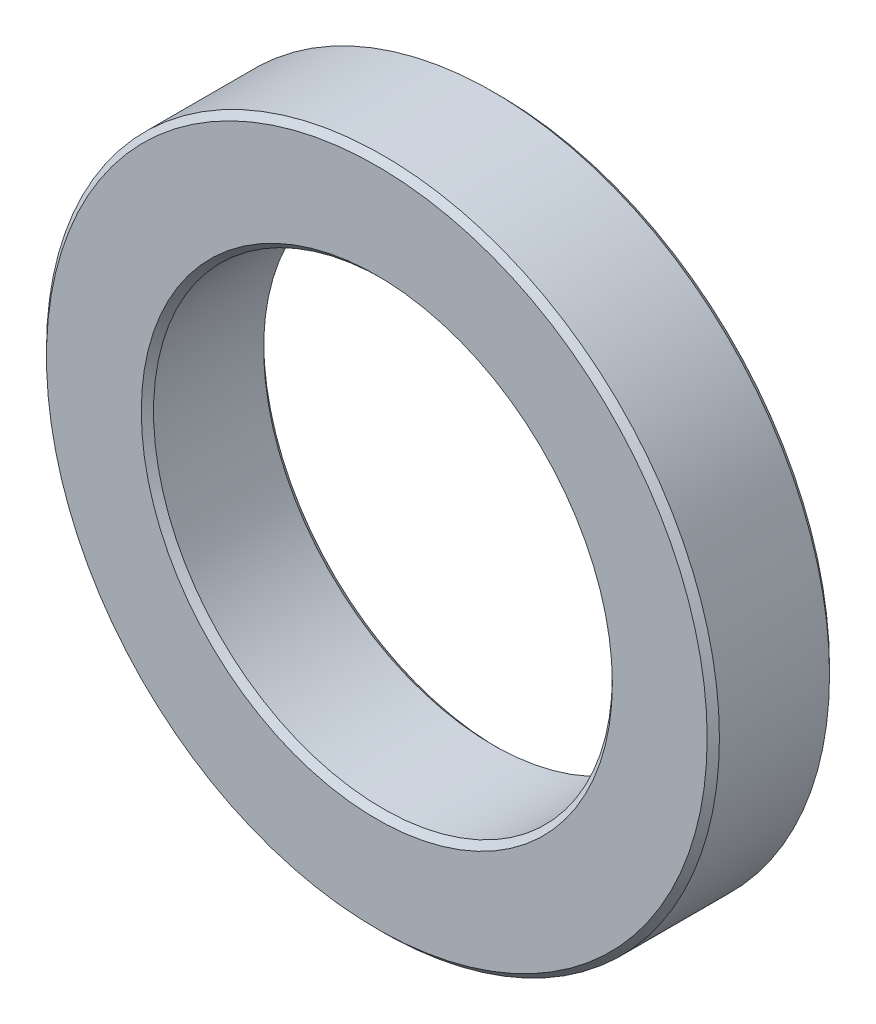
SolidWorks part; units mm, degrees
material "PA(尼龙6)"
ref_plane "前视基准面" through (0, 0, 0) normal (0, 0, 1) x (1, 0, 0)
ref_plane "上视基准面" through (0, 0, 0) normal (0, 1, 0) x (1, 0, 0)
ref_plane "右视基准面" through (0, 0, 0) normal (1, 0, 0) x (0, 0, -1)
sketch "草图1" plane through (0, 0, 0) normal (0, 0, 1) x (1, 0, 0)
  line L0 (-7.2812, 5.2901) -> (0, 0) construction
  line L1 (0, 0) -> (2.7812, 8.5595) construction
  line L5 (-7.2812, -5.2901) -> (0, 0) construction
  line L6 (0, 0) -> (2.7812, -8.5595) construction
  line L7 (0, 0) -> (9, 0) construction
  circle A0 centre (0, 0) radius 11
  circle A1 centre (9, 0) radius 1
  circle A2 centre (2.7812, -8.5595) radius 1
  circle A3 centre (-7.2812, -5.2901) radius 1
  circle A4 centre (-7.2812, 5.2901) radius 1
  circle A5 centre (2.7812, 8.5595) radius 1
  point P15 (0, 0)
  dimension "D1" = 5
  dimension "D2" = 2
  dimension "D4" = 22
  dimension "D3" = 9
extrude "凸台-拉伸1" add sketch "草图1" along normal blind 4
sketch "草图3" plane through (0, 0, 4) normal (0, 0, 1) x (1, 0, 0)
  circle A0 centre (2.7812, -8.5595) radius 1 construction
  circle A1 centre (9, 0) radius 1
  circle A2 centre (9, 0) radius 1
  circle A3 centre (-7.2812, -5.2901) radius 1 construction
  circle A4 centre (-7.2812, 5.2901) radius 1 construction
  circle A5 centre (2.7812, 8.5595) radius 1 construction
  circle A6 centre (2.7812, -8.5595) radius 1
  circle A7 centre (-7.2812, -5.2901) radius 1
  circle A8 centre (-7.2812, 5.2901) radius 1
  circle A9 centre (2.7812, 8.5595) radius 1
  dimension "D1" = 0
extrude "凸台-拉伸2" add sketch "草图3" against normal blind 12
sketch "草图12" plane through (0, 0, -8) normal (0, 0, -1) x (-1, 0, 0)
  circle A0 centre (-2.7812, -8.5595) radius 1 construction
  circle A1 centre (7.2812, 5.2901) radius 1 construction
  circle A2 centre (-2.7812, 8.5595) radius 1 construction
  circle A3 centre (-9, 0) radius 1 construction
  circle A4 centre (7.2812, -5.2901) radius 1 construction
  circle A5 centre (-2.7812, -8.5595) radius 1
  circle A6 centre (7.2812, 5.2901) radius 1
  circle A7 centre (-2.7812, 8.5595) radius 1
  circle A8 centre (-9, 0) radius 1
  circle A9 centre (7.2812, -5.2901) radius 1
extrude "切除-拉伸4" cut sketch "草图12" against normal blind 20
sketch "草图13" plane through (0, 0, 4) normal (0, 0, 1) x (1, 0, 0)
  circle A0 centre (0, 0) radius 7.5
  dimension "D1" = 15
extrude "切除-拉伸5" cut sketch "草图13" against normal through all
sketch "草图14" plane through (0, 0, 4) normal (0, 0, 1) x (1, 0, 0)
  circle A0 centre (-7.2812, -5.2901) radius 1 construction
  circle A1 centre (2.7812, -8.5595) radius 1 construction
  circle A2 centre (9, 0) radius 1 construction
  circle A3 centre (2.7812, 8.5595) radius 1 construction
  circle A4 centre (-7.2812, 5.2901) radius 1 construction
  circle A5 centre (-7.2812, -5.2901) radius 1
  circle A6 centre (2.7812, -8.5595) radius 1
  circle A7 centre (9, 0) radius 1
  circle A8 centre (2.7812, 8.5595) radius 1
  circle A9 centre (-7.2812, 5.2901) radius 1
extrude "凸台-拉伸3" add sketch "草图14" against normal blind 1
chamfer "倒角1" distance 0.2 angle 45 4 edges at (11, 0, 0) (11, 0, 4) (7.5, 0, 0) (7.5, 0, 4)
